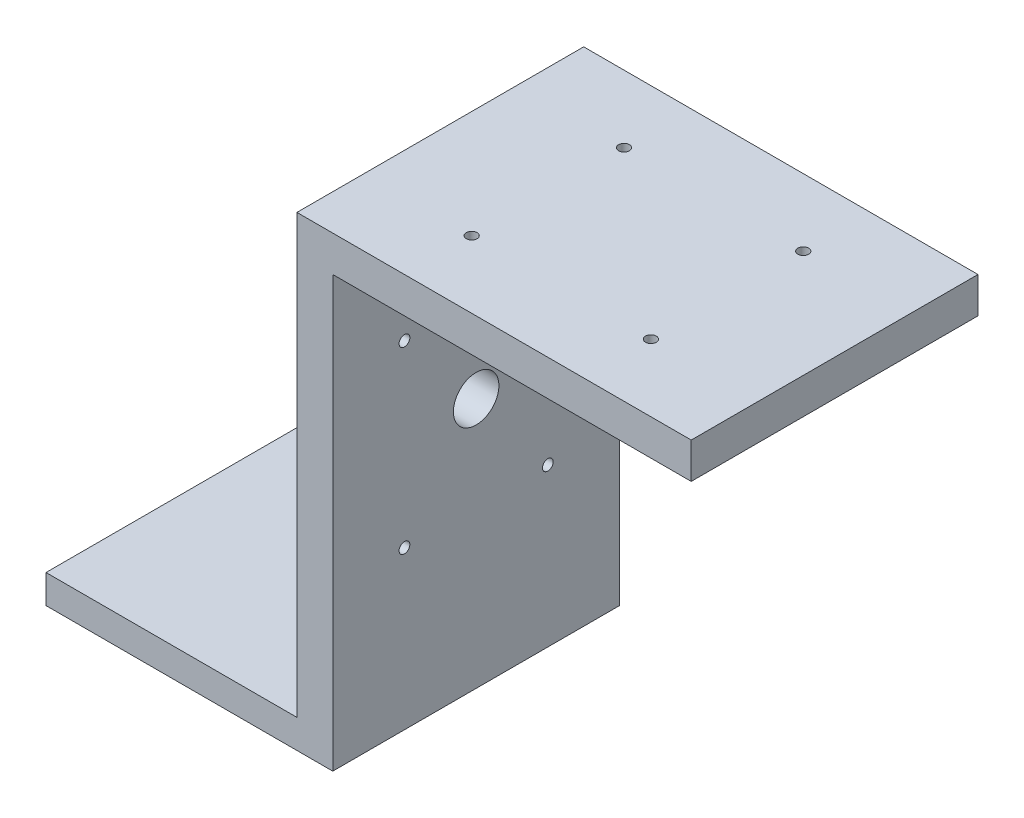
SolidWorks part; units mm, degrees
material "PLA"
ref_plane "Front Plane" through (0, 0, 0) normal (0, 0, 1) x (1, 0, 0)
ref_plane "Top Plane" through (0, 0, 0) normal (0, 1, 0) x (1, 0, 0)
ref_plane "Right Plane" through (0, 0, 0) normal (1, 0, 0) x (0, 0, -1)
sketch "Sketch1" plane through (0, 0, 0) normal (0, 0, 1) x (1, 0, 0)
  line L0 (0, 0) -> (-40, 0)
  line L1 (-40, 0) -> (-40, 4)
  line L2 (-40, 4) -> (-5, 4)
  line L3 (-5, 4) -> (-5, 55)
  line L4 (-5, 55) -> (50, 55)
  line L5 (50, 55) -> (50, 50)
  line L6 (50, 50) -> (0, 50)
  line L7 (0, 50) -> (0, 0)
  dimension "D1" = 55
  dimension "D2" = 55
  dimension "D3" = 5
  dimension "D4" = 4
  dimension "D5" = 40
  dimension "D6" = 5
extrude "Boss-Extrude1" add sketch "Sketch1" along normal mid plane 40
other "Move Face1" face at (22.5, 55, 0) parameters "D1"=10
other "Move Face2" face at (25, 50, 0) parameters "D1"=10
sketch "Sketch2" plane through (-5, 0, 0) normal (-1, 0, 0) x (0, 0, 1)
  line L0 (0, 0) -> (0, 65) construction
  line L1 (20, 65) -> (-20, 65) construction
  line L2 (-20, 34.5) -> (20, 34.5) construction
  line L3 (-20, 65) -> (-20, 4) construction
  line L4 (20, 65) -> (20, 4) construction
  line L6 (20, 65) -> (20, 4) construction
  circle A0 centre (-10, 22) radius 0.75
  circle A1 centre (10, 22) radius 0.75
  circle A2 centre (10, 47) radius 0.75
  circle A3 centre (-10, 47) radius 0.75
  point P11 (20, 34.5)
  dimension "D3" = 1.5
  dimension "D1" = 10
  dimension "D2" = 12.5
extrude "Cut-Extrude1" cut sketch "Sketch2" against normal through all
sketch "Sketch3" plane through (0, 65, -50) normal (0, -1, 0) x (1, 0, 0)
  line L0 (22.5, 30) -> (22.5, 70) construction
  line L2 (-5, 50) -> (50, 50) construction
  line L6 (50, 70) -> (50, 30) construction
  line L7 (50, 30) -> (-5, 30) construction
  line L8 (-5, 70) -> (-5, 30) construction
  circle A0 centre (10, 39.375) radius 0.75
  circle A1 centre (35, 39.375) radius 0.75
  circle A2 centre (35, 60.625) radius 0.75
  circle A3 centre (10, 60.625) radius 0.75
  dimension "D3" = 1.5
  dimension "D1" = 12.5
  dimension "D2" = 10.625
extrude "Cut-Extrude2" cut sketch "Sketch3" along normal through all
sketch "Sketch5" plane through (-5, 0, 0) normal (-1, 0, 0) x (0, 0, 1)
  line L1 (20, 4) -> (-20, 4) construction
  circle A0 centre (0, 35) radius 3.175
  dimension "D2" = 6.35
  dimension "D1" = 31
extrude "Cut-Extrude3" cut sketch "Sketch5" against normal through all
